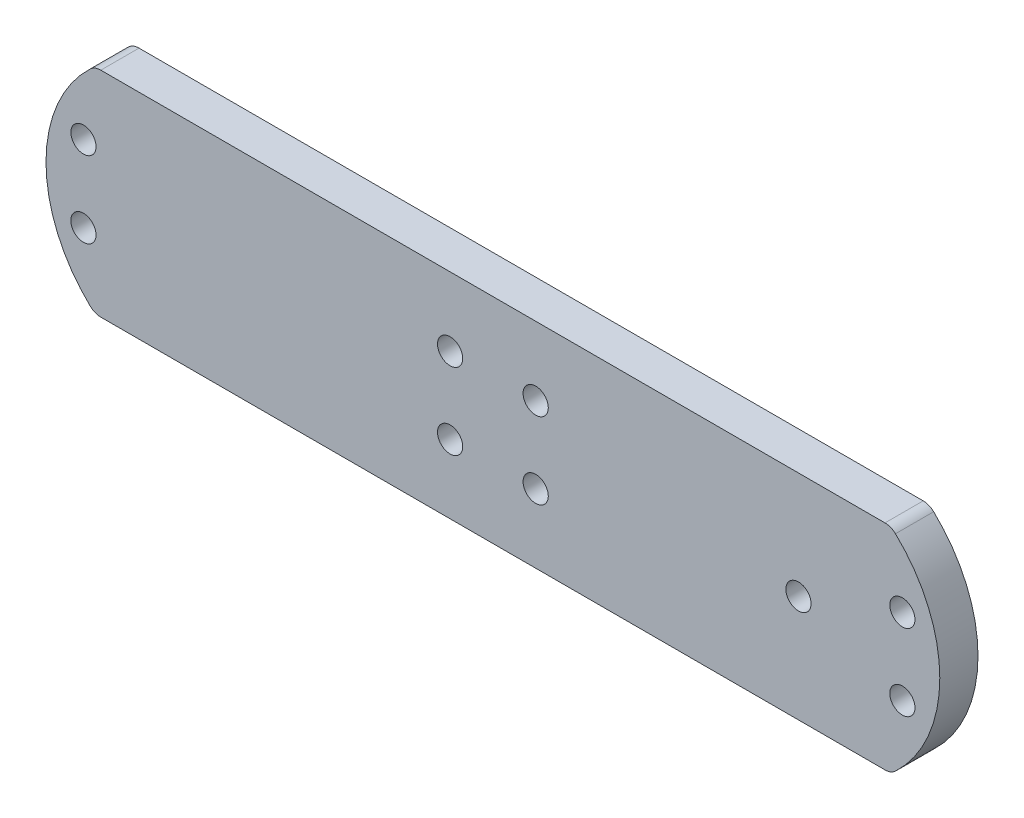
SolidWorks part; units mm, degrees
material "Alliage 1060"
ref_plane "Plan de face" through (0, 0, 0) normal (0, 0, 1) x (1, 0, 0)
ref_plane "Plan de dessus" through (0, 0, 0) normal (0, 1, 0) x (1, 0, 0)
ref_plane "Plan de droite" through (0, 0, 0) normal (1, 0, 0) x (0, 0, -1)
sketch "Esquisse1" plane through (0, 0, 0) normal (0, 0, 1) x (1, 0, 0)
  line L0 (11.3248, -14) -> (-91.3248, -14) construction
  line L1 (-91.3248, 14) -> (11.3248, 14) construction
  line L2 (11.3248, -14) -> (-91.3248, -14)
  line L3 (-91.3248, 14) -> (11.3248, 14)
  arc A0 (11.3248, -14) -> (12.6974, -13.4545) centre (11.3248, -12) ccw construction
  arc A1 (-92.6974, -13.4545) -> (-91.3248, -14) centre (-91.3248, -12) ccw construction
  arc A2 (-92.6974, 13.4545) -> (-92.6974, -13.4545) centre (-80, 0) ccw construction
  arc A3 (-91.3248, 14) -> (-92.6974, 13.4545) centre (-91.3248, 12) ccw construction
  arc A4 (12.6974, 13.4545) -> (11.3248, 14) centre (11.3248, 12) ccw construction
  arc A5 (12.6974, -13.4545) -> (12.6974, 13.4545) centre (0, 0) ccw construction
  arc A6 (11.3248, -14) -> (12.6974, -13.4545) centre (11.3248, -12) ccw
  arc A7 (-92.6974, -13.4545) -> (-91.3248, -14) centre (-91.3248, -12) ccw
  arc A8 (-92.6974, 13.4545) -> (-92.6974, -13.4545) centre (-80, 0) ccw
  arc A9 (-91.3248, 14) -> (-92.6974, 13.4545) centre (-91.3248, 12) ccw
  arc A10 (12.6974, 13.4545) -> (11.3248, 14) centre (11.3248, 12) ccw
  arc A11 (12.6974, -13.4545) -> (12.6974, 13.4545) centre (0, 0) ccw
extrude "Extrusion1" add sketch "Esquisse1" along normal blind 5
sketch "Esquisse2" plane through (0, 0, 0) normal (0, 0, -1) x (-1, 0, 0)
  line L0 (30.8, -7.95) -> (30.8, 7.95) construction
  line L1 (90, -7.95) -> (90, 7.95) construction
  line L2 (88, 9.95) -> (51.2154, 9.95) construction
  line L3 (51.2154, -9.95) -> (88, -9.95) construction
  line L4 (49.2154, 7.95) -> (49.2154, -7.95) construction
  line L5 (30.8, -7.95) -> (30.8, 7.95)
  line L6 (90, -7.95) -> (90, 7.95)
  line L7 (88, 9.95) -> (51.2154, 9.95)
  line L8 (51.2154, -9.95) -> (88, -9.95)
  line L9 (49.2154, 7.95) -> (49.2154, -7.95)
  line L10 (-8, -9.95) -> (28.8, -9.95) construction
  line L11 (-10, 7.95) -> (-10, -7.95) construction
  line L12 (28.8, 9.95) -> (-8, 9.95) construction
  line L13 (-8, -9.95) -> (28.8, -9.95)
  line L14 (-10, 7.95) -> (-10, -7.95)
  line L15 (28.8, 9.95) -> (-8, 9.95)
  arc A0 (30.8, 7.95) -> (28.8, 9.95) centre (28.8, 7.95) ccw construction
  arc A1 (28.8, -9.95) -> (30.8, -7.95) centre (28.8, -7.95) ccw construction
  arc A2 (88, -9.95) -> (90, -7.95) centre (88, -7.95) ccw construction
  arc A3 (90, 7.95) -> (88, 9.95) centre (88, 7.95) ccw construction
  arc A4 (51.2154, 9.95) -> (49.2154, 7.95) centre (51.2154, 7.95) ccw construction
  arc A5 (49.2154, -7.95) -> (51.2154, -9.95) centre (51.2154, -7.95) ccw construction
  arc A6 (30.8, 7.95) -> (28.8, 9.95) centre (28.8, 7.95) ccw
  arc A7 (28.8, -9.95) -> (30.8, -7.95) centre (28.8, -7.95) ccw
  arc A8 (88, -9.95) -> (90, -7.95) centre (88, -7.95) ccw
  arc A9 (90, 7.95) -> (88, 9.95) centre (88, 7.95) ccw
  arc A10 (51.2154, 9.95) -> (49.2154, 7.95) centre (51.2154, 7.95) ccw
  arc A11 (49.2154, -7.95) -> (51.2154, -9.95) centre (51.2154, -7.95) ccw
  arc A12 (-10, -7.95) -> (-8, -9.95) centre (-8, -7.95) ccw construction
  arc A13 (-8, 9.95) -> (-10, 7.95) centre (-8, 7.95) ccw construction
  arc A14 (-10, -7.95) -> (-8, -9.95) centre (-8, -7.95) ccw
  arc A15 (-8, 9.95) -> (-10, 7.95) centre (-8, 7.95) ccw
extrude "Extrusion2" [suppressed] cut sketch "Esquisse2" along normal through all
hole_wizard "Trou taraudé M3x0.51" positions "Esquisse4" profile "Esquisse3" tap size "M4x0.7" standard "Ansi Métrique" end condition through all
sketch "Esquisse4" plane through (0, 0, 5) normal (0, 0, 1) x (1, 0, 0)
  circle A0 centre (-93.6, -5) radius 2.1 construction
  circle A1 centre (-93.6, 5) radius 2.1 construction
  circle A2 centre (-45.6, 5) radius 2.1 construction
  circle A3 centre (-45.6, -5) radius 2.1 construction
  circle A4 centre (-34.4, -5) radius 2.1 construction
  circle A5 centre (-34.4, 5) radius 2.1 construction
  circle A6 centre (13.6, 5) radius 2.1 construction
  circle A7 centre (13.6, -5) radius 2.1 construction
  point P0 (-93.6, -5)
  point P1 (-93.6, 5)
  point P3 (-45.6, -5)
  point P5 (-45.6, 5)
  point P7 (-34.4, -5)
  point P9 (-34.4, 5)
  point P11 (13.6, -5)
  point P13 (13.6, 5)
sketch "Esquisse3" plane through (-93.6, -5, 5) normal (1, 0, 0) x (0, -1, 0)
  line L0 (0, 0) -> (0, 5)
  line L1 (0, 5) -> (1.65, 5)
  line L2 (1.65, 5) -> (1.65, 0)
  line L5 (1.65, 0) -> (0, 0)
  line L11 (0, -6.35) -> (0, 107.95) construction
  dimension "Diamètre du trou pour taraudage jusqu'au prochain" = 3.3
  dimension "Profondeur du trou pour taraudage jusqu'au prochain" = 5
cosmetic thread "Filetage de perçage1" parameters "D2"=4
cosmetic thread "Filetage de perçage2" parameters "D2"=4
cosmetic thread "Filetage de perçage3" parameters "D2"=4
cosmetic thread "Filetage de perçage4" parameters "D2"=4
cosmetic thread "Filetage de perçage5" parameters "D2"=4
cosmetic thread "Filetage de perçage6" parameters "D2"=4
cosmetic thread "Filetage de perçage7" parameters "D2"=4
cosmetic thread "Filetage de perçage8" parameters "D2"=4
hole_wizard "Trou taraudé M4x0.71" positions "Esquisse6" profile "Esquisse5" tap size "M4x0.7" standard "Ansi Métrique" end condition through all
sketch "Esquisse6" plane through (0, 0, 0) normal (0, 0, -1) x (-1, 0, 0)
  circle A2 centre (0, 0) radius 4 construction
  point P0 (0, 0)
sketch "Esquisse5" plane through (0, 0, 0) normal (1, 0, 0) x (0, 1, 0)
  line L0 (0, 0) -> (0, 5)
  line L1 (0, 5) -> (1.65, 5)
  line L2 (1.65, 5) -> (1.65, 0)
  line L5 (1.65, 0) -> (0, 0)
  line L11 (0, -6.35) -> (0, 107.95) construction
  dimension "Diamètre du trou pour taraudage jusqu'au prochain" = 3.3
  dimension "Profondeur du trou pour taraudage jusqu'au prochain" = 5
cosmetic thread "Filetage de perçage9" parameters "D2"=4
